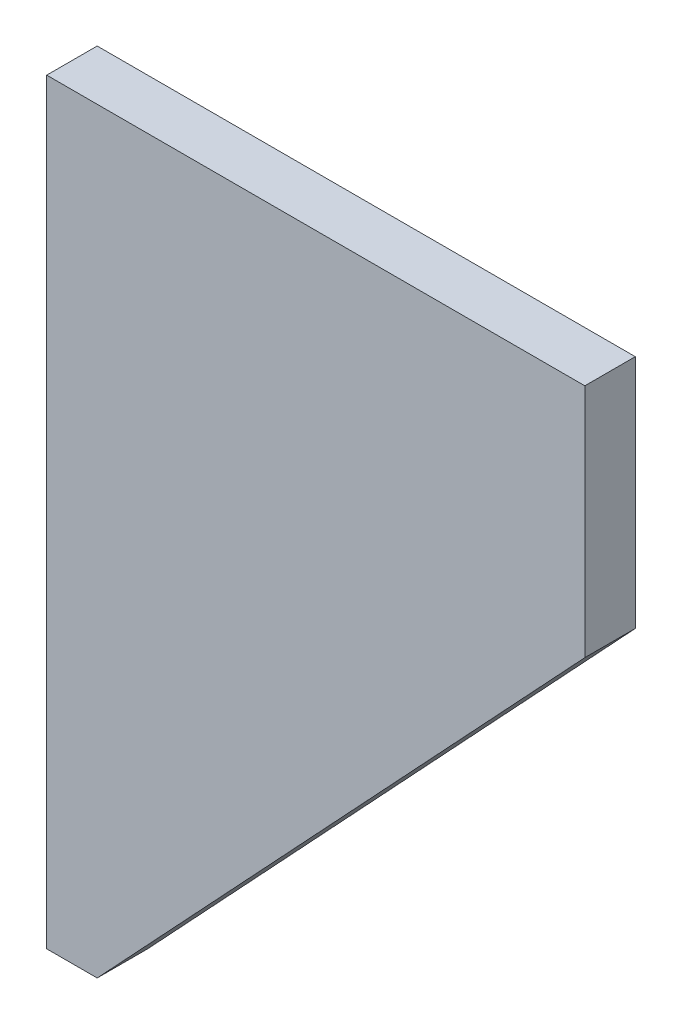
SolidWorks part; units mm, degrees
ref_plane "Front Plane" through (0, 0, 0) normal (0, 0, 1) x (1, 0, 0)
ref_plane "Top Plane" through (0, 0, 0) normal (0, 1, 0) x (1, 0, 0)
ref_plane "Right Plane" through (0, 0, 0) normal (1, 0, 0) x (0, 0, -1)
sketch "Sketch1" plane through (0, 0, 0) normal (0, 0, 1) x (1, 0, 0)
  line L0 (0, 0) -> (0, 285.75)
  line L1 (0, 285.75) -> (203.2, 285.75)
  line L2 (203.2, 285.75) -> (203.2, 196.85)
  line L3 (203.2, 196.85) -> (19.05, 0)
  line L4 (19.05, 0) -> (0, 0)
  dimension "D1" = 88.9
  dimension "D2" = 285.75
  dimension "D3" = 19.05
  dimension "D4" = 203.2
extrude "Boss-Extrude1" add sketch "Sketch1" along normal blind 19.05
